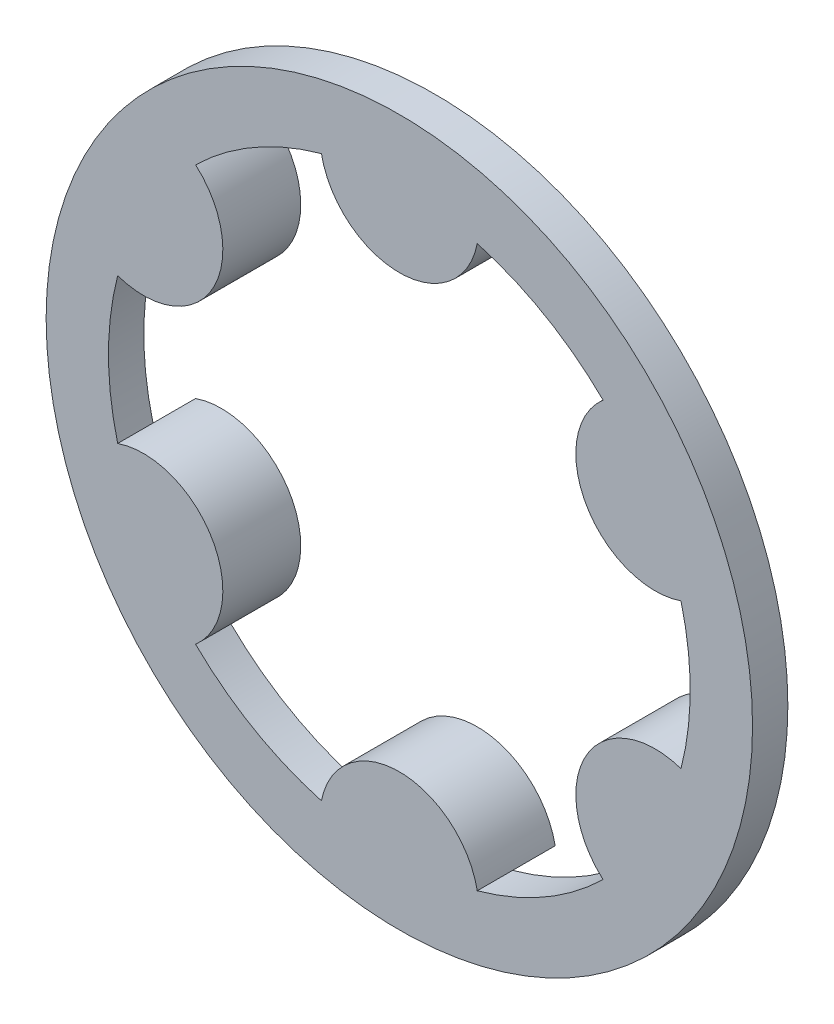
SolidWorks part; units mm, degrees
ref_plane "Спереди" through (0, 0, 0) normal (0, 0, 1) x (1, 0, 0)
ref_plane "Сверху" through (0, 0, 0) normal (0, 1, 0) x (1, 0, 0)
ref_plane "Справа" through (0, 0, 0) normal (1, 0, 0) x (0, 0, -1)
sketch "Эскиз1" plane through (0, 0, 0) normal (0, 0, 1) x (1, 0, 0)
  circle A0 centre (0, 0) radius 34
  circle A1 centre (0, 0) radius 28
  dimension "D1" = 68
  dimension "D2" = 56
extrude "Бобышка-Вытянуть1" add sketch "Эскиз1" along normal blind 3.4
sketch "Эскиз2" plane through (0, 0, 3.4) normal (0, 0, 1) x (1, 0, 0)
  arc A0 (-7.5, 26.9768) -> (7.5, 26.9768) centre (0, 28.4417) ccw
  circle A1 centre (0, 0) radius 28 construction
  arc A2 (19.6126, 19.9836) -> (27.1126, 6.9932) centre (24.6313, 14.2209) ccw
  arc A3 (27.1126, -6.9932) -> (19.6126, -19.9836) centre (24.6313, -14.2209) ccw
  arc A4 (7.5, -26.9768) -> (-7.5, -26.9768) centre (0, -28.4417) ccw
  arc A5 (-19.6126, -19.9836) -> (-27.1126, -6.9932) centre (-24.6313, -14.2209) ccw
  arc A6 (-27.1126, 6.9932) -> (-19.6126, 19.9836) centre (-24.6313, 14.2209) ccw
  arc A7 (-7.5, 26.9768) -> (7.5, 26.9768) centre (0, 0) cw
  arc A8 (19.6126, 19.9836) -> (27.1126, 6.9932) centre (0, 0) cw
  arc A9 (27.1126, -6.9932) -> (19.6126, -19.9836) centre (0, 0) cw
  arc A10 (7.5, -26.9768) -> (-7.5, -26.9768) centre (0, 0) cw
  arc A11 (-19.6126, -19.9836) -> (-27.1126, -6.9932) centre (0, 0) cw
  arc A12 (-27.1126, 6.9932) -> (-19.6126, 19.9836) centre (0, 0) cw
  point P23 (0, 0)
  point P35 (0, 0)
  dimension "D2" = 7.2
  dimension "D1" = 15
  dimension "D3" = 6
  dimension "D4" = 6
extrude "Бобышка-Вытянуть2" add sketch "Эскиз2" against normal blind 7.5 contours A6 A12
